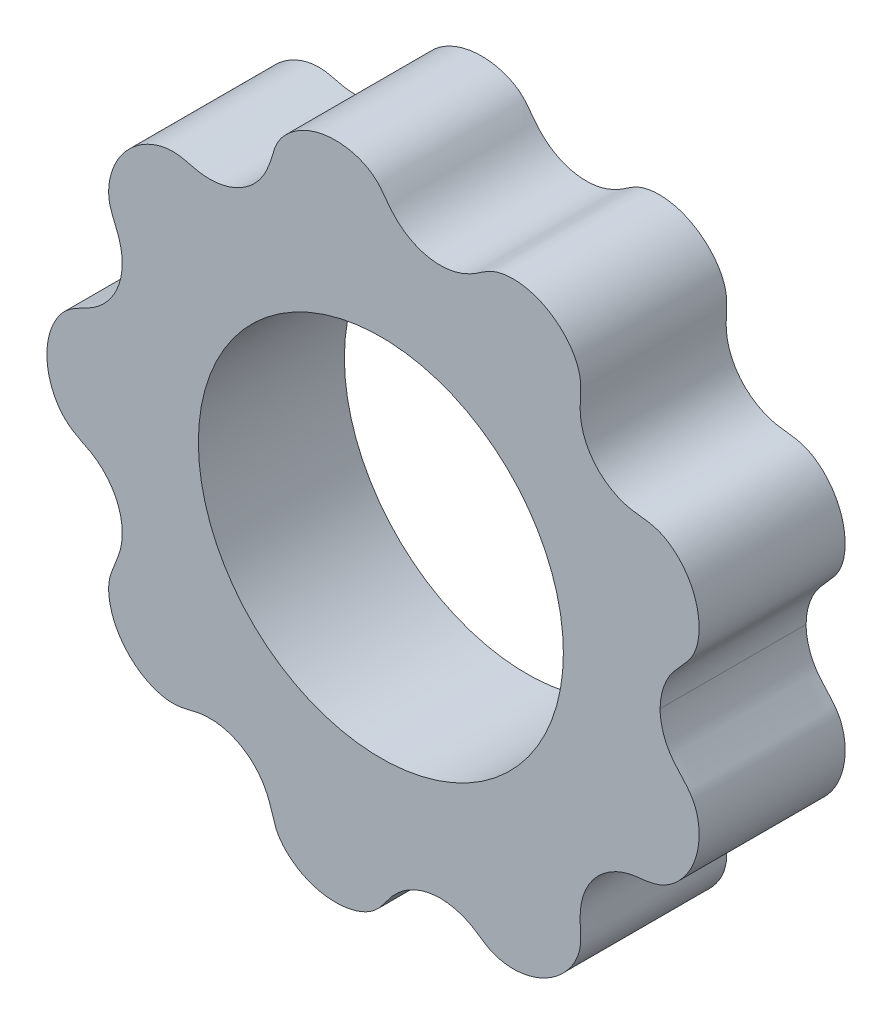
SolidWorks part; units mm, degrees
ref_plane "Plan de face" through (0, 0, 0) normal (0, 0, 1) x (1, 0, 0)
ref_plane "Plan de dessus" through (0, 0, 0) normal (0, 1, 0) x (1, 0, 0)
ref_plane "Plan de droite" through (0, 0, 0) normal (1, 0, 0) x (0, 0, -1)
sketch "Esquisse1" plane through (0, 0, 0) normal (0, 0, 1) x (1, 0, 0)
  line L0 (-1000, 0) -> (49000, 0) construction
  circle A0 centre (0, 0) radius 5
  spline S0 degree 4 poles (8.7803, 2.0844) (8.759, 1.978) (8.7116, 1.8178) (8.6208, 1.6087) (8.4352, 1.3623) (8.2291, 1.1723) (8.0546, 0.9611) (7.9309, 0.754) (7.8577, 0.5838) (7.8163, 0.4608) (7.7897, 0.3601) (7.7696, 0.2597) (7.7562, 0.1563) (7.7491, 0.0328) (7.7496, -0.0491) (7.7588, -0.1913) (7.7779, -0.3065) (7.8056, -0.4254) (7.841, -0.5373) (7.8831, -0.6437) (7.9405, -0.7643) (8.0051, -0.8752) (8.0749, -0.9763) (8.1479, -1.0682) (8.2211, -1.1528) (8.3136, -1.2502) (8.4331, -1.3675) (8.5597, -1.5239) (8.6668, -1.7139) (8.7499, -1.9332) (8.8131, -2.2165) (8.8306, -2.5628) (8.778, -2.9416) (8.6388, -3.3355) (8.4213, -3.7041) (8.1416, -4.0116) (7.8245, -4.2297) (7.4913, -4.3566) (7.1957, -4.385) (6.9323, -4.4107) (6.6448, -4.4834) (6.3462, -4.6152) (6.0562, -4.8275) (5.8056, -5.1258) (5.6474, -5.4483) (5.5685, -5.7654) (5.5509, -6.0274) (5.559, -6.2259) (5.5768, -6.424) (5.5841, -6.6544) (5.5247, -6.9709) (5.364, -7.3215) (5.1104, -7.6501) (4.7959, -7.9189) (4.46, -8.1128) (4.07, -8.2508) (3.6586, -8.3061) (3.2746, -8.27) (2.9708, -8.1632) (2.775, -8.0416) (2.6123, -7.9272) (2.4444, -7.8209) (2.2088, -7.7052) (1.8946, -7.6149) (1.5364, -7.5907) (1.1524, -7.6584) (0.8241, -7.8037) (0.5597, -7.996) (0.3779, -8.1853) (0.2565, -8.3426) (0.1428, -8.5058) (0.0003, -8.687) (-0.2486, -8.8913) (-0.5971, -9.0565) (-1.0026, -9.1453) (-1.4163, -9.149) (-1.7983, -9.0816) (-2.1858, -8.9366) (-2.5365, -8.7145) (-2.8074, -8.4401) (-2.9714, -8.1629) (-3.0433, -7.944) (-3.0944, -7.7517) (-3.1547, -7.5624) (-3.2608, -7.3223) (-3.4435, -7.0512) (-3.7022, -6.8024) (-4.04, -6.6075) (-4.3848, -6.5077) (-4.711, -6.4851) (-4.9719, -6.5132) (-5.166, -6.5557) (-5.358, -6.6076) (-5.5836, -6.6548) (-5.9057, -6.6513) (-6.2788, -6.5539) (-6.6465, -6.3612) (-6.9658, -6.0981) (-7.2151, -5.801) (-7.4187, -5.4409) (-7.5446, -5.0453) (-7.5758, -4.661) (-7.5233, -4.3432) (-7.4376, -4.1292) (-7.3531, -3.9491) (-7.2776, -3.7654) (-7.2046, -3.5133) (-7.1703, -3.1881) (-7.2096, -2.8216) (-7.3528, -2.4379) (-7.5822, -2.113) (-7.8731, -1.8612) (-8.1648, -1.6988) (-8.4272, -1.5882) (-8.635, -1.4411) (-8.7928, -1.2863) (-8.9216, -1.1185) (-9.0241, -0.9478) (-9.1056, -0.7696) (-9.1676, -0.5968) (-9.2112, -0.4121) (-9.2383, -0.2591) (-9.2499, -0.0714) (-9.2511, 0.0231) (-9.2456, 0.1474) (-9.236, 0.2528) (-9.2216, 0.3507) (-9.2023, 0.4489) (-9.1722, 0.5713) (-9.1226, 0.7275) (-9.0436, 0.9139) (-8.9291, 1.1109) (-8.7889, 1.2906) (-8.642, 1.4324) (-8.4961, 1.5394) (-8.3465, 1.6201) (-8.2018, 1.6867) (-8.0955, 1.7412) (-8.0264, 1.7808) (-7.9923, 1.8014) knots 0 0 0 0 0 0.012017 0.018525 0.025033 0.034045 0.043057 0.048815 0.051694 0.054573 0.057453 0.060333 0.063213 0.066093 0.069526 0.072959 0.076393 0.079826 0.08291 0.085994 0.089079 0.094647 0.097131 0.099614 0.102098 0.107066 0.112033 0.118191 0.124349 0.131165 0.13798 0.150298 0.162615 0.173316 0.184016 0.19759 0.208293 0.215687 0.22308 0.230394 0.237707 0.24842 0.259137 0.269855 0.280567 0.287881 0.295194 0.298891 0.302588 0.309981 0.320684 0.334258 0.344959 0.355659 0.36636 0.37706 0.390635 0.401338 0.408731 0.412428 0.416125 0.423438 0.430751 0.441464 0.452182 0.462899 0.473612 0.480925 0.488239 0.491935 0.495632 0.503026 0.513729 0.527303 0.538003 0.548704 0.559404 0.570105 0.583679 0.594382 0.601775 0.605472 0.609169 0.616482 0.623796 0.634508 0.645226 0.655944 0.666656 0.67397 0.681283 0.68498 0.688676 0.69607 0.706773 0.720347 0.731048 0.741748 0.752449 0.763149 0.776723 0.787426 0.79482 0.798517 0.802213 0.809527 0.81684 0.827553 0.83827 0.850051 0.861806 0.871198 0.880589 0.886967 0.893346 0.899224 0.905101 0.910307 0.915512 0.920718 0.925923 0.930358 0.934792 0.937583 0.940373 0.943163 0.945953 0.948743 0.951534 0.957114 0.964137 0.97116 0.976742 0.982324 0.986743 0.991162 0.995581 1 1 1 1 1 construction
  spline S1 degree 4 poles (7.75, 0) (7.75, -0.0269) (7.7516, -0.0801) (7.7588, -0.1913) (7.7779, -0.3065) (7.8056, -0.4254) (7.841, -0.5373) (7.8831, -0.6437) (7.9405, -0.7643) (8.0051, -0.8752) (8.0749, -0.9763) (8.1479, -1.0682) (8.2211, -1.1528) (8.3136, -1.2502) (8.4331, -1.3675) (8.5597, -1.5239) (8.6668, -1.7139) (8.7499, -1.9332) (8.8131, -2.2165) (8.8306, -2.5628) (8.778, -2.9416) (8.6388, -3.3355) (8.4213, -3.7041) (8.1416, -4.0116) (7.8245, -4.2297) (7.4913, -4.3566) (7.1957, -4.385) (6.9323, -4.4107) (6.6448, -4.4834) (6.3462, -4.6152) (6.0562, -4.8275) (5.8056, -5.1258) (5.6474, -5.4483) (5.5685, -5.7654) (5.5509, -6.0274) (5.559, -6.2259) (5.5768, -6.424) (5.5841, -6.6544) (5.5247, -6.9709) (5.364, -7.3215) (5.1104, -7.6501) (4.7959, -7.9189) (4.46, -8.1128) (4.07, -8.2508) (3.6586, -8.3061) (3.2746, -8.27) (2.9708, -8.1632) (2.775, -8.0416) (2.6123, -7.9272) (2.4444, -7.8209) (2.2088, -7.7052) (1.8946, -7.6149) (1.5364, -7.5907) (1.1524, -7.6584) (0.8241, -7.8037) (0.5597, -7.996) (0.3779, -8.1853) (0.2565, -8.3426) (0.1428, -8.5058) (0.0003, -8.687) (-0.2486, -8.8913) (-0.5971, -9.0565) (-1.0026, -9.1453) (-1.4163, -9.149) (-1.7983, -9.0816) (-2.1858, -8.9366) (-2.5365, -8.7145) (-2.8074, -8.4401) (-2.9714, -8.1629) (-3.0433, -7.944) (-3.0944, -7.7517) (-3.1547, -7.5624) (-3.2608, -7.3223) (-3.4435, -7.0512) (-3.7022, -6.8024) (-4.04, -6.6075) (-4.3848, -6.5077) (-4.711, -6.4851) (-4.9719, -6.5132) (-5.166, -6.5557) (-5.358, -6.6076) (-5.5836, -6.6548) (-5.9057, -6.6513) (-6.2788, -6.5539) (-6.6465, -6.3612) (-6.9658, -6.0981) (-7.2151, -5.801) (-7.4187, -5.4409) (-7.5446, -5.0453) (-7.5758, -4.661) (-7.5233, -4.3432) (-7.4376, -4.1292) (-7.3531, -3.9491) (-7.2776, -3.7654) (-7.2046, -3.5133) (-7.1703, -3.1881) (-7.2096, -2.8216) (-7.3528, -2.4379) (-7.5822, -2.113) (-7.8731, -1.8612) (-8.1648, -1.6988) (-8.4272, -1.5882) (-8.635, -1.4411) (-8.7928, -1.2863) (-8.9216, -1.1185) (-9.0241, -0.9478) (-9.1056, -0.7696) (-9.1676, -0.5968) (-9.2112, -0.4121) (-9.2383, -0.2591) (-9.248, -0.1025) (-9.25, -0.0347) (-9.25, 0) knots 0.066093 0.066093 0.066093 0.066093 0.066093 0.069526 0.072959 0.076393 0.079826 0.08291 0.085994 0.089079 0.094647 0.097131 0.099614 0.102098 0.107066 0.112033 0.118191 0.124349 0.131165 0.13798 0.150298 0.162615 0.173316 0.184016 0.19759 0.208293 0.215687 0.22308 0.230394 0.237707 0.24842 0.259137 0.269855 0.280567 0.287881 0.295194 0.298891 0.302588 0.309981 0.320684 0.334258 0.344959 0.355659 0.36636 0.37706 0.390635 0.401338 0.408731 0.412428 0.416125 0.423438 0.430751 0.441464 0.452182 0.462899 0.473612 0.480925 0.488239 0.491935 0.495632 0.503026 0.513729 0.527303 0.538003 0.548704 0.559404 0.570105 0.583679 0.594382 0.601775 0.605472 0.609169 0.616482 0.623796 0.634508 0.645226 0.655944 0.666656 0.67397 0.681283 0.68498 0.688676 0.69607 0.706773 0.720347 0.731048 0.741748 0.752449 0.763149 0.776723 0.787426 0.79482 0.798517 0.802213 0.809527 0.81684 0.827553 0.83827 0.850051 0.861806 0.871198 0.880589 0.886967 0.893346 0.899224 0.905101 0.910307 0.915512 0.920718 0.925923 0.930358 0.934792 0.934792 0.934792 0.934792 0.934792 construction
  spline S2 degree 4 poles (7.75, 0) (7.75, 0.0269) (7.7516, 0.0801) (7.7588, 0.1913) (7.7779, 0.3065) (7.8056, 0.4254) (7.841, 0.5373) (7.8831, 0.6437) (7.9405, 0.7643) (8.0051, 0.8752) (8.0749, 0.9763) (8.1479, 1.0682) (8.2211, 1.1528) (8.3136, 1.2502) (8.4331, 1.3675) (8.5597, 1.5239) (8.6668, 1.7139) (8.7499, 1.9332) (8.8131, 2.2165) (8.8306, 2.5628) (8.778, 2.9416) (8.6388, 3.3355) (8.4213, 3.7041) (8.1416, 4.0116) (7.8245, 4.2297) (7.4913, 4.3566) (7.1957, 4.385) (6.9323, 4.4107) (6.6448, 4.4834) (6.3462, 4.6152) (6.0562, 4.8275) (5.8056, 5.1258) (5.6474, 5.4483) (5.5685, 5.7654) (5.5509, 6.0274) (5.559, 6.2259) (5.5768, 6.424) (5.5841, 6.6544) (5.5247, 6.9709) (5.364, 7.3215) (5.1104, 7.6501) (4.7959, 7.9189) (4.46, 8.1128) (4.07, 8.2508) (3.6586, 8.3061) (3.2746, 8.27) (2.9708, 8.1632) (2.775, 8.0416) (2.6123, 7.9272) (2.4444, 7.8209) (2.2088, 7.7052) (1.8946, 7.6149) (1.5364, 7.5907) (1.1524, 7.6584) (0.8241, 7.8037) (0.5597, 7.996) (0.3779, 8.1853) (0.2565, 8.3426) (0.1428, 8.5058) (0.0003, 8.687) (-0.2486, 8.8913) (-0.5971, 9.0565) (-1.0026, 9.1453) (-1.4163, 9.149) (-1.7983, 9.0816) (-2.1858, 8.9366) (-2.5365, 8.7145) (-2.8074, 8.4401) (-2.9714, 8.1629) (-3.0433, 7.944) (-3.0944, 7.7517) (-3.1547, 7.5624) (-3.2608, 7.3223) (-3.4435, 7.0512) (-3.7022, 6.8024) (-4.04, 6.6075) (-4.3848, 6.5077) (-4.711, 6.4851) (-4.9719, 6.5132) (-5.166, 6.5557) (-5.358, 6.6076) (-5.5836, 6.6548) (-5.9057, 6.6513) (-6.2788, 6.5539) (-6.6465, 6.3612) (-6.9658, 6.0981) (-7.2151, 5.801) (-7.4187, 5.4409) (-7.5446, 5.0453) (-7.5758, 4.661) (-7.5233, 4.3432) (-7.4376, 4.1292) (-7.3531, 3.9491) (-7.2776, 3.7654) (-7.2046, 3.5133) (-7.1703, 3.1881) (-7.2096, 2.8216) (-7.3528, 2.4379) (-7.5822, 2.113) (-7.8731, 1.8612) (-8.1648, 1.6988) (-8.4272, 1.5882) (-8.635, 1.4411) (-8.7928, 1.2863) (-8.9216, 1.1185) (-9.0241, 0.9478) (-9.1056, 0.7696) (-9.1676, 0.5968) (-9.2112, 0.4121) (-9.2383, 0.2591) (-9.248, 0.1025) (-9.25, 0.0347) (-9.25, 0) knots 0.066093 0.066093 0.066093 0.066093 0.066093 0.069526 0.072959 0.076393 0.079826 0.08291 0.085994 0.089079 0.094647 0.097131 0.099614 0.102098 0.107066 0.112033 0.118191 0.124349 0.131165 0.13798 0.150298 0.162615 0.173316 0.184016 0.19759 0.208293 0.215687 0.22308 0.230394 0.237707 0.24842 0.259137 0.269855 0.280567 0.287881 0.295194 0.298891 0.302588 0.309981 0.320684 0.334258 0.344959 0.355659 0.36636 0.37706 0.390635 0.401338 0.408731 0.412428 0.416125 0.423438 0.430751 0.441464 0.452182 0.462899 0.473612 0.480925 0.488239 0.491935 0.495632 0.503026 0.513729 0.527303 0.538003 0.548704 0.559404 0.570105 0.583679 0.594382 0.601775 0.605472 0.609169 0.616482 0.623796 0.634508 0.645226 0.655944 0.666656 0.67397 0.681283 0.68498 0.688676 0.69607 0.706773 0.720347 0.731048 0.741748 0.752449 0.763149 0.776723 0.787426 0.79482 0.798517 0.802213 0.809527 0.81684 0.827553 0.83827 0.850051 0.861806 0.871198 0.880589 0.886967 0.893346 0.899224 0.905101 0.910307 0.915512 0.920718 0.925923 0.930358 0.934792 0.934792 0.934792 0.934792 0.934792 construction
  spline S3 degree 1 poles (7.65, 0) (-9.15, 0) knots 0 0 1 1 construction
  spline S4 degree 1 poles (7.65, 0) (-9.15, 0) knots 0 0 1 1 construction
  spline S5 degree 3 poles (7.65, 0) (7.65, 0.3408) (7.8098, 0.8699) (8.2973, 1.3646) (8.6717, 1.828) (8.7831, 2.6376) (8.5305, 3.3888) (8.1407, 3.8756) (7.7627, 4.1565) (7.3383, 4.2872) (6.6589, 4.3181) (5.8584, 4.7576) (5.453, 5.5666) (5.4572, 6.2693) (5.5047, 6.879) (5.1067, 7.5875) (4.4533, 8.036) (3.848, 8.1914) (3.3794, 8.1898) (2.9459, 8.0584) (2.5618, 7.7538) (2.0783, 7.5424) (1.383, 7.4623) (0.7011, 7.7054) (0.2114, 8.2113) (-0.1292, 8.7502) (-0.8552, 9.0773) (-1.6511, 9.0424) (-2.2286, 8.802) (-2.6017, 8.5215) (-2.8866, 8.1566) (-2.9939, 7.7006) (-3.1913, 7.2112) (-3.6388, 6.6728) (-4.2986, 6.3773) (-5.0016, 6.3971) (-5.4766, 6.5533) (-5.925, 6.5512) (-6.52, 6.3553) (-7.0089, 5.9463) (-7.3258, 5.4066) (-7.4571, 4.9596) (-7.4718, 4.4901) (-7.3011, 4.0739) (-7.1001, 3.5882) (-7.0658, 3.0647) (-7.1841, 2.5522) (-7.4539, 2.1016) (-7.8414, 1.7461) (-8.3141, 1.5373) (-8.6819, 1.2898) (-9.0415, 0.7761) (-9.15, 0.307) (-9.15, 0) knots 0.066093 0.066093 0.066093 0.066093 0.09324 0.106813 0.120387 0.147533 0.17468 0.188254 0.201827 0.215401 0.228974 0.256121 0.283268 0.296841 0.310415 0.337561 0.364708 0.378282 0.391855 0.405429 0.419002 0.432576 0.446149 0.473296 0.486869 0.500443 0.52759 0.554736 0.56831 0.581883 0.595457 0.60903 0.622604 0.636177 0.663324 0.676897 0.690471 0.704044 0.717618 0.744764 0.758338 0.771911 0.785485 0.799058 0.812632 0.826205 0.839778 0.853352 0.866925 0.880499 0.894072 0.907646 0.934792 0.934792 0.934792 0.934792
  spline S6 degree 3 poles (-9.15, 0) (-9.15, -0.307) (-9.0415, -0.7761) (-8.6819, -1.2898) (-8.3141, -1.5373) (-7.8414, -1.7461) (-7.4539, -2.1016) (-7.1841, -2.5522) (-7.0658, -3.0647) (-7.1001, -3.5882) (-7.3011, -4.0739) (-7.4718, -4.4901) (-7.4571, -4.9596) (-7.3258, -5.4066) (-7.0089, -5.9463) (-6.52, -6.3553) (-5.925, -6.5512) (-5.4766, -6.5533) (-5.0016, -6.3971) (-4.2986, -6.3773) (-3.6388, -6.6728) (-3.1913, -7.2112) (-2.9939, -7.7006) (-2.8866, -8.1566) (-2.6017, -8.5215) (-2.2286, -8.802) (-1.6511, -9.0424) (-0.8552, -9.0773) (-0.1292, -8.7502) (0.2114, -8.2113) (0.7011, -7.7054) (1.383, -7.4623) (2.0783, -7.5424) (2.5618, -7.7538) (2.9459, -8.0584) (3.3794, -8.1898) (3.848, -8.1914) (4.4533, -8.036) (5.1067, -7.5875) (5.5047, -6.879) (5.4572, -6.2693) (5.453, -5.5666) (5.8584, -4.7576) (6.6589, -4.3181) (7.3383, -4.2872) (7.7627, -4.1565) (8.1407, -3.8756) (8.5305, -3.3888) (8.7831, -2.6376) (8.6717, -1.828) (8.2973, -1.3646) (7.8098, -0.8699) (7.65, -0.3408) (7.65, 0) knots 0.066093 0.066093 0.066093 0.066093 0.09324 0.106813 0.120387 0.13396 0.147533 0.161107 0.17468 0.188254 0.201827 0.215401 0.228974 0.242547 0.256121 0.283268 0.296841 0.310415 0.323988 0.337561 0.364708 0.378282 0.391855 0.405429 0.419002 0.432576 0.446149 0.473296 0.500443 0.514016 0.52759 0.554736 0.56831 0.581883 0.595457 0.60903 0.622604 0.636177 0.663324 0.690471 0.704044 0.717618 0.744764 0.771911 0.785485 0.799058 0.812632 0.826205 0.853352 0.880499 0.894072 0.907646 0.934792 0.934792 0.934792 0.934792
  dimension "D1" = 10
  dimension "D2" = 0.1
extrude "Boss.-Extru.4" add sketch "Esquisse1" along normal blind 4
equation "\"R\"= 10'Radius of the rotor"
equation "\"E\"= 0.75'Eccentricity from input shaft to center of rotor"
equation "\"Rr\"= 1.5'Roller radius"
equation "\"N\"= 10'Amount of rollers"
